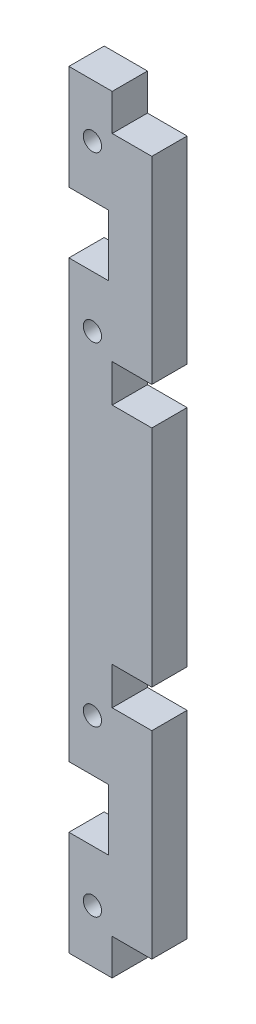
SolidWorks part; units mm, degrees
ref_plane "Płaszczyzna przednia" through (0, 0, 0) normal (0, 0, 1) x (1, 0, 0)
ref_plane "Płaszczyzna górna" through (0, 0, 0) normal (0, 1, 0) x (1, 0, 0)
ref_plane "Płaszczyzna prawa" through (0, 0, 0) normal (1, 0, 0) x (0, 0, -1)
sketch "Szkic1" plane through (0, 0, 0) normal (0, 0, 1) x (1, 0, 0)
  line L0 (-79.4505, -66.58) -> (-79.4505, 70)
  line L1 (-79.4505, -66.58) -> (-65.3505, -66.58)
  line L2 (-79.4505, 70) -> (-65.3505, 70)
  line L3 (-65.3505, -66.58) -> (-65.3505, 70)
  line L4 (-71.8889, -66.58) -> (-65.3389, -66.58) construction
  line L5 (-65.3389, 70) -> (-71.8889, 70) construction
  line L9 (-79.4505, 6) -> (-79.4505, 0) construction
  dimension "D1" = 0
  dimension "D2" = 0
  dimension "D3" = 14.1
  dimension "D4" = 0
extrude "Dodanie-wyciągnięcie1" add sketch "Szkic1" against normal blind 6
other "Przenieś ścianę1" face at (-72.4005, -66.58, -3) parameters "D1"=6
sketch "Szkic2" plane through (0, 0, 0) normal (0, 0, 1) x (1, 0, 0)
  line L0 (-65.3505, 70) -> (-79.4505, 70) construction
  line L1 (-71.8889, 70) -> (-65.3389, 70)
  line L2 (-71.8889, 70) -> (-71.8889, 64)
  line L3 (-71.8889, 64) -> (-65.3389, 64)
  line L4 (-65.3389, 70) -> (-65.3389, 64)
  line L5 (-65.3389, 0) -> (-65.3389, 6) construction
  line L6 (-79.4505, 52.2) -> (-79.4505, 41.8)
  line L10 (-65.3389, 30) -> (-71.8889, 30) construction
  line L11 (-71.8889, 30) -> (-71.8889, 24) construction
  line L12 (-79.4505, -60.58) -> (-65.3505, -60.58) construction
  line L13 (-71.9005, -60.58) -> (-65.3505, -60.58)
  line L14 (-71.9005, -60.58) -> (-71.9005, -54.6371)
  line L15 (-71.9005, -54.6371) -> (-65.3505, -54.6371)
  line L16 (-65.3505, -60.58) -> (-65.3505, -54.6371)
  line L17 (-72.1005, -60.78) -> (-72.1005, -54.4371)
  line L19 (-79.4505, 70) -> (-79.4505, -60.58) construction
  line L22 (-72.1005, -54.4371) -> (-65.1505, -54.4371)
  line L23 (-65.1505, -60.78) -> (-65.1505, -54.4371)
  line L24 (-72.1005, -60.78) -> (-65.1505, -60.78)
  line L29 (-72.0889, 70.2) -> (-72.0889, 63.8)
  line L30 (-72.0889, 63.8) -> (-65.1389, 63.8)
  line L31 (-65.1389, 70.2) -> (-65.1389, 63.8)
  line L32 (-72.0889, 70.2) -> (-65.1389, 70.2)
  line L40 (-65.3505, -60.58) -> (-65.3505, 70) construction
  line L41 (-71.8889, 24) -> (-65.3389, 24) construction
  line L42 (-65.3389, 24) -> (-65.3389, 30) construction
  line L44 (-71.8889, -20.58) -> (-71.8889, -26.58) construction
  line L46 (-65.3389, 30) -> (-71.8889, 30)
  line L47 (-71.8889, 30) -> (-71.8889, 24)
  line L48 (-71.8889, 24) -> (-65.3389, 24)
  line L49 (-65.3389, 24) -> (-65.3389, 30)
  line L50 (-71.8889, -26.58) -> (-65.3389, -26.58)
  line L51 (-71.8889, -20.58) -> (-71.8889, -26.58)
  line L52 (-65.3389, -20.58) -> (-71.8889, -20.58)
  line L53 (-65.3389, -26.58) -> (-65.3389, -20.58)
  line L54 (-72.0889, 30.2) -> (-72.0889, 23.8)
  line L55 (-72.0889, 23.8) -> (-65.1389, 23.8)
  line L56 (-65.1389, 23.8) -> (-65.1389, 30.2)
  line L57 (-65.1389, 30.2) -> (-72.0889, 30.2)
  line L58 (-72.0889, -20.38) -> (-72.0889, -26.78)
  line L59 (-72.0889, -26.78) -> (-65.1389, -26.78)
  line L60 (-65.1389, -26.78) -> (-65.1389, -20.38)
  line L61 (-65.1389, -20.38) -> (-72.0889, -20.38)
  line L66 (-79.4505, 52.2) -> (-72.7005, 52.2) construction
  line L67 (-72.7005, 52.2) -> (-72.7005, 41.8) construction
  line L68 (-72.7005, 41.8) -> (-96.9505, 41.8) construction
  line L69 (-79.4505, 52.2) -> (-72.7005, 52.2)
  line L74 (-72.7005, 52.2) -> (-72.7005, 41.8)
  line L75 (-72.7005, 41.8) -> (-79.4505, 41.8)
  line L76 (-79.4505, -32.3903) -> (-72.7005, -32.3903) construction
  line L77 (-79.4505, -32.3903) -> (-72.7005, -32.3903)
  line L78 (-72.7005, -32.3903) -> (-72.7005, -42.7903) construction
  line L79 (-72.7005, -42.7903) -> (-79.4505, -42.7903) construction
  line L80 (-72.7005, -32.3903) -> (-72.7005, -42.7903)
  line L81 (-72.7005, -42.7903) -> (-79.4505, -42.7903)
  line L82 (-79.4505, -32.3903) -> (-79.4505, -42.7903)
  dimension "D1" = 0
  dimension "D2" = 6.55
  dimension "D5" = 6
  dimension "D7" = 6.55
  dimension "D8" = 5.9429
  dimension "D10" = 0
  dimension "D11" = 0.2
  dimension "D12" = 0.2
sketch "Szkic3" plane through (0, 0, 0) normal (0, 0, 1) x (1, 0, 0)
  line L0 (-72.0889, 70.2) -> (-72.0889, 63.8) construction
  line L1 (-72.0889, 63.8) -> (-65.1389, 63.8) construction
  line L2 (-65.1389, 70.2) -> (-65.1389, 63.8) construction
  line L3 (-72.0889, 70.2) -> (-65.1389, 70.2) construction
  line L4 (-79.4505, 52.2) -> (-79.4505, 41.8) construction
  line L5 (-79.4505, 52.2) -> (-79.4505, 41.8)
  line L6 (-71.8889, -20.58) -> (-65.3389, -20.58) construction
  line L8 (-79.4505, -32.3903) -> (-72.7005, -32.3903) construction
  line L9 (-79.4505, -32.3903) -> (-72.7005, -32.3903)
  line L10 (-79.4505, -32.3903) -> (-79.4505, -42.7903) construction
  line L11 (-72.7005, -42.7903) -> (-79.4505, -42.7903) construction
  line L12 (-65.1389, 30.2) -> (-72.0889, 30.2) construction
  line L13 (-72.0889, 30.2) -> (-72.0889, 23.8) construction
  line L14 (-72.0889, 23.8) -> (-65.1389, 23.8) construction
  line L15 (-65.1389, 23.8) -> (-65.1389, 30.2) construction
  line L16 (-72.1005, -60.78) -> (-72.1005, -54.4371) construction
  line L17 (-72.1005, -54.4371) -> (-65.1505, -54.4371) construction
  line L18 (-65.1505, -60.78) -> (-65.1505, -54.4371) construction
  line L19 (-72.1005, -60.78) -> (-65.1505, -60.78) construction
  line L24 (-72.0889, 70.2) -> (-72.0889, 63.8)
  line L25 (-72.0889, 63.8) -> (-65.1389, 63.8)
  line L26 (-65.1389, 70.2) -> (-65.1389, 63.8)
  line L27 (-72.0889, 70.2) -> (-65.1389, 70.2)
  line L28 (-65.1389, 30.2) -> (-72.0889, 30.2)
  line L29 (-72.0889, 30.2) -> (-72.0889, 23.8)
  line L30 (-72.0889, 23.8) -> (-65.1389, 23.8)
  line L31 (-65.1389, 23.8) -> (-65.1389, 30.2)
  line L32 (-72.1005, -60.78) -> (-72.1005, -54.4371)
  line L33 (-72.1005, -54.4371) -> (-65.1505, -54.4371)
  line L34 (-65.1505, -60.78) -> (-65.1505, -54.4371)
  line L35 (-72.1005, -60.78) -> (-65.1505, -60.78)
  line L36 (-65.1389, -14.38) -> (-72.0889, -14.38)
  line L37 (-72.0889, -14.38) -> (-72.0889, -20.78)
  line L38 (-72.0889, -20.78) -> (-65.1389, -20.78)
  line L39 (-65.1389, -20.78) -> (-65.1389, -14.38)
  line L44 (-72.7005, -32.3903) -> (-72.7005, -42.7903) construction
  line L46 (-79.4505, 52.2) -> (-72.7005, 52.2) construction
  line L47 (-72.7005, 52.2) -> (-72.7005, 41.8) construction
  line L48 (-72.7005, 41.8) -> (-79.4505, 41.8) construction
  line L49 (-79.4505, -32.3903) -> (-79.4505, -42.7903)
  line L50 (-72.7005, -42.7903) -> (-79.4505, -42.7903)
  line L51 (-72.7005, -32.3903) -> (-72.7005, -42.7903)
  line L53 (-79.4505, 52.2) -> (-72.7005, 52.2)
  line L54 (-72.7005, 52.2) -> (-72.7005, 41.8)
  line L55 (-72.7005, 41.8) -> (-79.4505, 41.8)
  dimension "D1" = 6.4
  dimension "D2" = 6.95
  dimension "D3" = 0.2
extrude "Wytnij-wyciągnięcie1" cut sketch "Szkic3" against normal through all
sketch "Szkic4" plane through (0, 0, 0) normal (0, 0, 1) x (1, 0, 0)
  line L0 (-79.4505, 70) -> (-79.4505, 52.2) construction
  line L1 (-72.0889, 70) -> (-79.4505, 70) construction
  line L2 (-79.4505, -60.58) -> (-72.1005, -60.58) construction
  line L3 (-79.4505, -42.7903) -> (-79.4505, -60.58) construction
  circle A0 centre (-75.4505, 61) radius 1.55
  circle A1 centre (-75.4505, -51.58) radius 1.55
  circle A2 centre (-75.4505, 33) radius 1.55
  circle A3 centre (-75.4505, -23.58) radius 1.55
  dimension "D1" = 4
  dimension "D2" = 4
  dimension "D3" = 9
  dimension "D4" = 9
  dimension "D5" = 3.1
  dimension "D6" = 3.1
  dimension "D7" = 3.1
  dimension "D8" = 0
  dimension "D9" = 28
  dimension "D10" = 3.1
  dimension "D11" = 4
  dimension "D12" = 28
extrude "Wytnij-wyciągnięcie2" cut sketch "Szkic4" against normal through all
equation "\"tolerancja_wpusy\"=0.2"
equation "\"dlugosc_wpustu_duzy\"=20"
equation "\"srednica_otworu_M3\"=3.1"
equation "\"szerokosc_nogi_T\"=3.1"
equation "\"dlugosc_T_30\"=11"
equation "\"grubosc_na_nakretke_kwadrat\"=2"
equation "\"szerokosc_na_nakretke_kwadrat\"=5.85"
equation "\"wyokosc_nadstawki_T\"=0.5"
equation "\"dlugosc_T_20_6\"=14"
equation "\"D5@Szkic4\"=\"srednica_otworu_M3\""
equation "\"D6@Szkic4\"=\"srednica_otworu_M3\""
equation "\"D7@Szkic4\"=\"srednica_otworu_M3\""
equation "\"D10@Szkic4\"=\"srednica_otworu_M3\""
